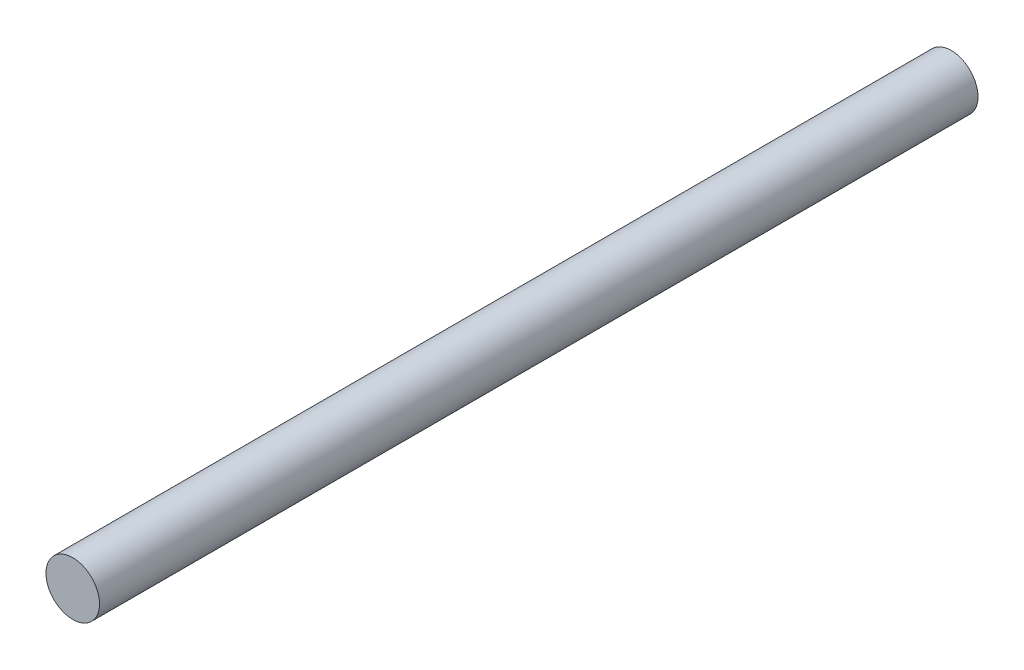
SolidWorks part; units mm, degrees
material "201 Annealed Stainless Steel (SS)"
ref_plane "Front Plane" through (0, 0, 0) normal (0, 0, 1) x (1, 0, 0)
ref_plane "Top Plane" through (0, 0, 0) normal (0, 1, 0) x (1, 0, 0)
ref_plane "Right Plane" through (0, 0, 0) normal (1, 0, 0) x (0, 0, -1)
sketch "Sketch1" plane through (0, 0, 0) normal (0, 0, 1) x (1, 0, 0)
  circle A0 centre (0, 0) radius 2.5
  dimension "D1" = 5
extrude "Boss-Extrude1" add sketch "Sketch1" along normal mid plane 82
cosmetic thread "Cosmetic Thread1" parameters "D1"=10, "D2"=4.11
cosmetic thread "Cosmetic Thread2" parameters "D1"=15, "D2"=4.11
